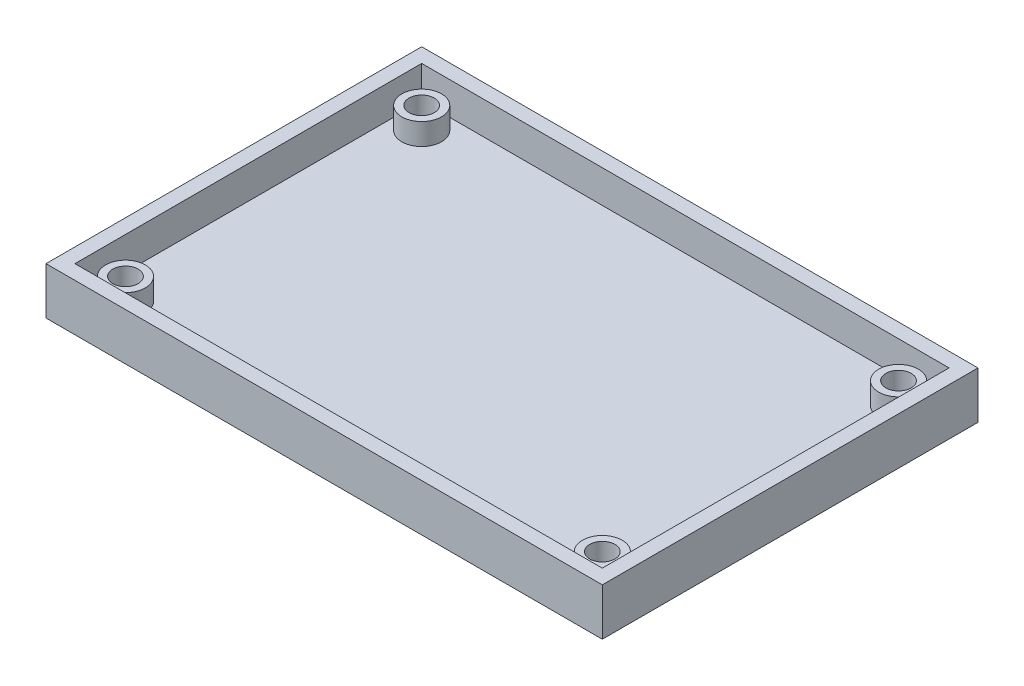
SolidWorks part; units mm, degrees
ref_plane "Front Plane" through (0, 0, 0) normal (0, 0, 1) x (1, 0, 0)
ref_plane "Top Plane" through (0, 0, 0) normal (0, 1, 0) x (1, 0, 0)
ref_plane "Right Plane" through (0, 0, 0) normal (1, 0, 0) x (0, 0, -1)
sketch "Sketch1" plane through (0, 0, 0) normal (0, 1, 0) x (1, 0, 0)
  line L1 (-36.5, 24) -> (36.5, 24)
  line L2 (-36.5, 24) -> (-36.5, -24)
  line L3 (-36.5, -24) -> (36.5, -24)
  line L4 (36.5, 24) -> (36.5, -24)
  line L5 (-36.5, 24) -> (36.5, -24) construction
  line L6 (-36.5, -24) -> (36.5, 24) construction
  line L7 (-38.5, 26) -> (38.5, 26)
  line L8 (-38.5, 26) -> (-38.5, -26)
  line L9 (-38.5, -26) -> (38.5, -26)
  line L10 (38.5, 26) -> (38.5, -26)
  line L11 (-38.5, 26) -> (38.5, -26) construction
  line L12 (-38.5, -26) -> (38.5, 26) construction
  point P0 (0, 0)
  point P6 (0, 0)
  dimension "D1" = 73
  dimension "D2" = 48
  dimension "D3" = 2
  dimension "D4" = 2
extrude "Boss-Extrude1" add sketch "Sketch1" along normal blind 4.524
sketch "Sketch2" plane through (0, 0, 0) normal (0, -1, 0) x (1, 0, 0)
  line L1 (38.5, 26) -> (-38.5, 26)
  line L2 (38.5, 26) -> (38.5, -26)
  line L3 (38.5, -26) -> (-38.5, -26)
  line L4 (-38.5, 26) -> (-38.5, -26)
  line L5 (38.5, 26) -> (-38.5, -26) construction
  line L6 (38.5, -26) -> (-38.5, 26) construction
  point P0 (0, 0)
extrude "Boss-Extrude2" add sketch "Sketch2" along normal blind 2
sketch "Sketch3" plane through (0, 0, 0) normal (0, 1, 0) x (1, 0, 0)
  line L0 (36.5, 24) -> (-36.5, 24) construction
  line L1 (-36.5, 24) -> (-36.5, -24) construction
  line L2 (-36.5, -24) -> (36.5, -24) construction
  line L3 (36.5, -24) -> (36.5, 24) construction
  circle A0 centre (-33, 20.5) radius 1.75
  circle A1 centre (33, 20.5) radius 1.75
  circle A2 centre (33, -20.5) radius 1.75
  circle A3 centre (-33, -20.5) radius 1.75
  dimension "D1" = 3.5
  dimension "D2" = 3.5
  dimension "D3" = 3.5
  dimension "D4" = 3.5
  dimension "D5" = 3.5
  dimension "D6" = 3.5
  dimension "D7" = 3.5
  dimension "D8" = 3.5
  dimension "D9" = 3.5
  dimension "D10" = 3.5
  dimension "D11" = 3.5
  dimension "D12" = 3.5
extrude "Cut-Extrude1" cut sketch "Sketch3" against normal blind 2
sketch "Sketch4" plane through (0, 0, 0) normal (0, 1, 0) x (1, 0, 0)
  circle A0 centre (-33, -20.5) radius 2.75
  circle A1 centre (-33, -20.5) radius 1.75
  circle A2 centre (33, -20.5) radius 1.75
  circle A3 centre (33, -20.5) radius 2.75
  circle A4 centre (33, 20.5) radius 1.75
  circle A5 centre (33, 20.5) radius 2.75
  circle A6 centre (-33, 20.5) radius 1.75
  circle A7 centre (-33, 20.5) radius 2.75
  dimension "D1" = 1
  dimension "D2" = 1
  dimension "D3" = 1
  dimension "D4" = 1
extrude "Boss-Extrude3" add sketch "Sketch4" along normal blind 3
